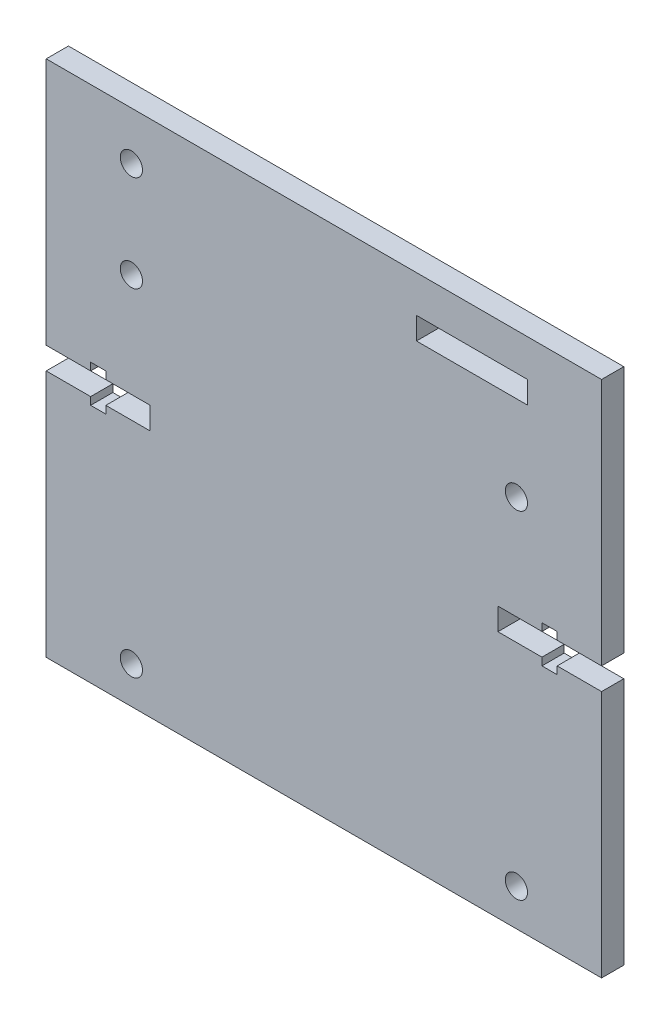
SolidWorks part; units mm, degrees
ref_plane "Front Plane" through (0, 0, 0) normal (0, 0, 1) x (1, 0, 0)
ref_plane "Top Plane" through (0, 0, 0) normal (0, 1, 0) x (1, 0, 0)
ref_plane "Right Plane" through (0, 0, 0) normal (1, 0, 0) x (0, 0, -1)
sketch "Esquisse1" plane through (0, 0, 0) normal (0, 0, 1) x (1, 0, 0)
  line L1 (-50.1837, 32.1633) -> (24.8163, 32.1633)
  line L2 (-50.1837, 32.1633) -> (-50.1837, -37.8367)
  line L3 (-50.1837, -37.8367) -> (24.8163, -37.8367)
  line L4 (24.8163, 32.1633) -> (24.8163, -37.8367)
  line L9 (-0.1837, 27.1633) -> (14.8163, 27.1633)
  line L10 (-0.1837, 27.1633) -> (-0.1837, 24.1633)
  line L11 (-0.1837, 24.1633) -> (14.8163, 24.1633)
  line L12 (14.8163, 27.1633) -> (14.8163, 24.1633)
  circle A0 centre (-38.6837, 25.6633) radius 1.5
  circle A1 centre (-38.6837, 12.6633) radius 1.5
  circle A2 centre (13.3163, 12.6633) radius 1.5
  circle A3 centre (-38.6837, -32.8367) radius 1.5
  circle A4 centre (13.3163, -32.8367) radius 1.5
  dimension "D3" = 11.5
  dimension "D6" = 1.5
  dimension "D7" = 11.5
  dimension "D10" = 5
  dimension "D11" = 19.5
  dimension "D1" = 75
  dimension "D2" = 70
  dimension "D4" = 3
  dimension "D5" = 5
  dimension "D8" = 11.5
  dimension "D9" = 10
extrude "Boss.-Extru.1" add sketch "Esquisse1" along normal blind 3
sketch "Esquisse2" plane through (0, 0, 0) normal (0, 0, 1) x (1, 0, 0)
  line L0 (24.8163, -1.3367) -> (18.8163, -1.3367)
  line L1 (24.8163, -37.8367) -> (24.8163, 32.1633) construction
  line L2 (18.8163, -1.3367) -> (18.8163, -0.3117)
  line L3 (18.8163, -0.3117) -> (16.7663, -0.3117)
  line L4 (16.7663, -0.3117) -> (16.7663, -1.3367)
  line L5 (16.7663, -1.3367) -> (10.8163, -1.3367)
  line L6 (10.8163, -1.3367) -> (10.8163, -4.3367)
  line L7 (10.8163, -4.3367) -> (16.7663, -4.3367)
  line L8 (16.7663, -4.3367) -> (16.7663, -5.3617)
  line L9 (16.7663, -5.3617) -> (18.8163, -5.3617)
  line L10 (18.8163, -5.3617) -> (18.8163, -4.3367)
  line L11 (18.8163, -4.3367) -> (24.8163, -4.3367)
  line L12 (24.8163, -1.3367) -> (24.8163, -4.3367)
  line L13 (24.8163, 32.1633) -> (-50.1837, 32.1633) construction
  line L14 (-12.6837, 32.1633) -> (-12.6837, -47.9061) construction
  line L15 (-50.1837, -1.3367) -> (-50.1837, -4.3367)
  line L16 (-44.1837, -4.3367) -> (-50.1837, -4.3367)
  line L17 (-44.1837, -5.3617) -> (-44.1837, -4.3367)
  line L18 (-42.1337, -5.3617) -> (-44.1837, -5.3617)
  line L19 (-42.1337, -4.3367) -> (-42.1337, -5.3617)
  line L20 (-36.1837, -4.3367) -> (-42.1337, -4.3367)
  line L21 (-36.1837, -1.3367) -> (-36.1837, -4.3367)
  line L22 (-42.1337, -1.3367) -> (-36.1837, -1.3367)
  line L23 (-42.1337, -0.3117) -> (-42.1337, -1.3367)
  line L24 (-44.1837, -0.3117) -> (-42.1337, -0.3117)
  line L25 (-44.1837, -1.3367) -> (-44.1837, -0.3117)
  line L26 (-50.1837, -1.3367) -> (-44.1837, -1.3367)
  dimension "D1" = 3
  dimension "D2" = 3
  dimension "D3" = 5.05
  dimension "D4" = 1.025
  dimension "D5" = 1.025
  dimension "D6" = 33.5
  dimension "D7" = 2.05
  dimension "D8" = 2.05
  dimension "D9" = 6
  dimension "D10" = 14
extrude "Enlèv. mat.-Extru.2" cut sketch "Esquisse2" against normal blind 10 and the other way blind 10
